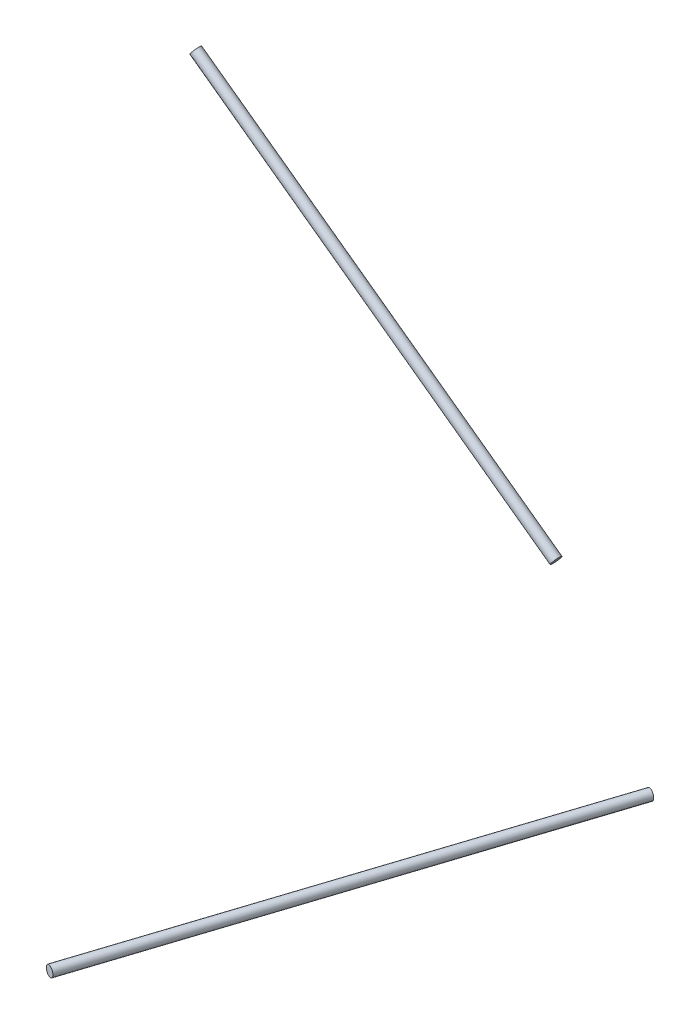
SolidWorks part; units mm, degrees
ref_plane "Front Plane" through (0, 0, 0) normal (0, 0, 1) x (1, 0, 0)
ref_plane "Top Plane" through (0, 0, 0) normal (0, 1, 0) x (1, 0, 0)
ref_plane "Right Plane" through (0, 0, 0) normal (1, 0, 0) x (0, 0, -1)
sketch "Sketch2" plane through (0, 0, 0) normal (0, 0, 1) x (1, 0, 0)
  line L0 (178.7928, 134.6028) -> (72.7649, 211.6366)
  line L1 (182.0288, -132.2517) -> (225, 0) construction
  line L2 (225, 0) -> (182.0288, 132.2517) construction
  line L3 (182.0288, 132.2517) -> (69.5288, 213.9877) construction
  line L4 (69.5288, 213.9877) -> (-69.5288, 213.9877) construction
  line L5 (-69.5288, 213.9877) -> (-182.0288, 132.2517) construction
  line L6 (-182.0288, 132.2517) -> (-225, 0) construction
  line L7 (-225, 0) -> (-182.0288, -132.2517) construction
  line L8 (-182.0288, -132.2517) -> (-69.5288, -213.9877) construction
  line L9 (-69.5288, -213.9877) -> (69.5288, -213.9877) construction
  line L10 (69.5288, -213.9877) -> (182.0288, -132.2517) construction
  line L11 (112.5, 81.736) -> (69.5288, 213.9877) construction
  line L12 (69.5288, 213.9877) -> (-69.5288, 213.9877) construction
  line L13 (-69.5288, 213.9877) -> (-112.5, 81.736) construction
  line L14 (-112.5, 81.736) -> (0, 0) construction
  line L15 (0, 0) -> (112.5, 81.736) construction
  circle A0 centre (0, 0) radius 225 construction
  circle A1 centre (0, 0) radius 213.9877 construction
  circle A2 centre (0, 118.2895) radius 95.6982 construction
  point P16 (0, 225)
  point P24 (0, 213.9877)
  dimension "D1" = 450
  dimension "D2" = 4
  dimension "D3" = 4
ref_plane "Plane1" through (72.7649, 211.6366, 0) normal (-0.809, 0.5878, 0) x (0, 0, 1)
sketch "Sketch3" plane through (72.7649, 211.6366, 0) normal (-0.809, 0.5878, 0) x (0, 0, 1)
  circle A0 centre (0, 0) radius 1.5
  dimension "D1" = 3
sweep "Sweep1" add profiles "Sketch3" path "Sketch2"
sketch "Sketch4" plane through (0, 0, 0) normal (0, 1, 0) x (1, 0, 0)
  line L0 (74.325, -44.5904) -> (117.6888, 88.8696)
  point P4 (0, 0)
ref_plane "Plane2" through (74.325, 0, 44.5904) normal (0.309, 0, -0.9511) x (-0.9511, 0, -0.309)
sketch "Sketch5" plane through (74.325, 0, 44.5904) normal (0.309, 0, -0.9511) x (-0.9511, 0, -0.309)
  circle A0 centre (0, 0) radius 1.5
  dimension "D1" = 3
sweep "Sweep2" add profiles "Sketch5" path "Sketch4"
